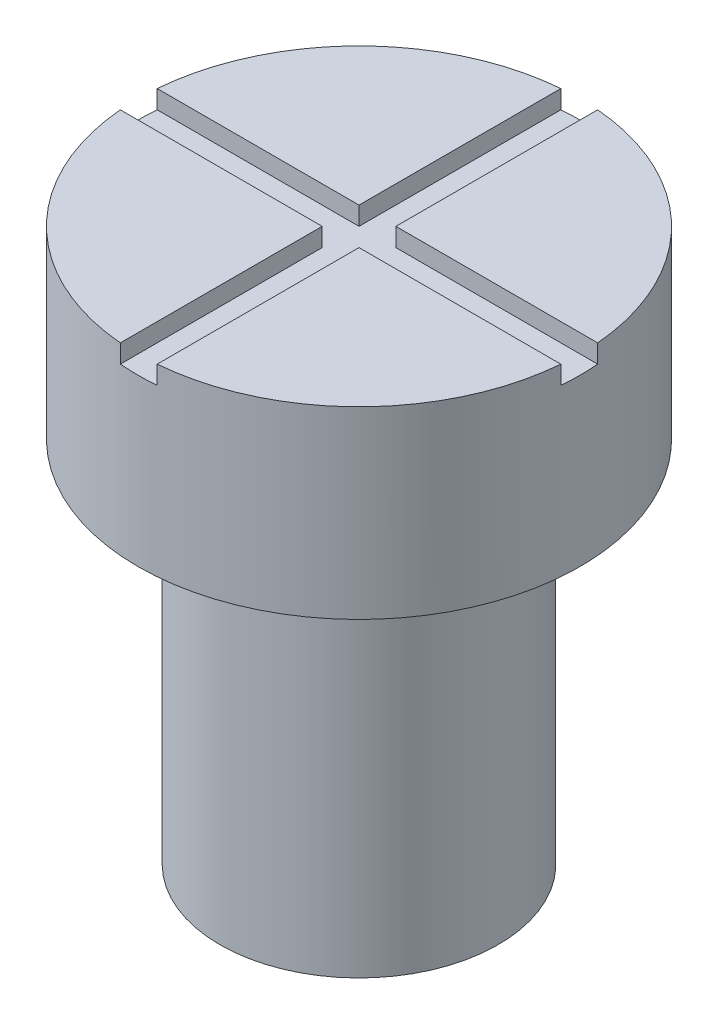
SolidWorks part; units mm, degrees
material "6061 Alloy"
ref_plane "Front Plane" through (0, 0, 0) normal (0, 0, 1) x (1, 0, 0)
ref_plane "Top Plane" through (0, 0, 0) normal (0, 1, 0) x (1, 0, 0)
ref_plane "Right Plane" through (0, 0, 0) normal (1, 0, 0) x (0, 0, -1)
sketch "Sketch1" plane through (0, 0, 0) normal (0, 1, 0) x (1, 0, 0)
  circle A0 centre (-36.5816, 71.105) radius 0.7556
extrude "Boss-Extrude1" add sketch "Sketch1" along normal blind 2
sketch "Sketch2" plane through (0, 2, 0) normal (0, 1, 0) x (1, 0, 0)
  circle A0 centre (-36.5816, 71.105) radius 1.2
extrude "Boss-Extrude2" add sketch "Sketch2" along normal blind 1
sketch "Sketch3" plane through (0, 3, 0) normal (0, 1, 0) x (1, 0, 0)
  line L0 (-36.6816, 72.305) -> (-36.4816, 72.305)
  line L1 (-36.4816, 72.305) -> (-36.4685, 72.3065)
  line L2 (-36.4816, 72.305) -> (-36.4816, 71.205)
  line L3 (-36.6816, 72.305) -> (-36.6816, 71.205)
  line L4 (-37.7816, 71.005) -> (-36.6816, 71.005)
  line L5 (-37.7816, 71.205) -> (-36.6816, 71.205)
  line L6 (-35.3816, 71.205) -> (-35.3816, 71.005)
  line L7 (-36.6816, 69.905) -> (-36.4816, 69.905)
  line L8 (-36.4816, 71.005) -> (-36.4816, 69.905)
  line L9 (-37.7816, 71.205) -> (-37.7816, 71.005)
  line L10 (-36.4816, 71.205) -> (-35.3816, 71.205)
  line L12 (-36.4816, 71.005) -> (-35.3816, 71.005)
  line L14 (-36.6816, 71.005) -> (-36.6816, 69.905)
  circle M1 centre (-36.5816, 71.105) radius 1.2
extrude "Cut-Extrude1" cut sketch "Sketch3" against normal blind 0.1 contours L4 L14 L8 L12 L10 L2 L3 L5 M1
